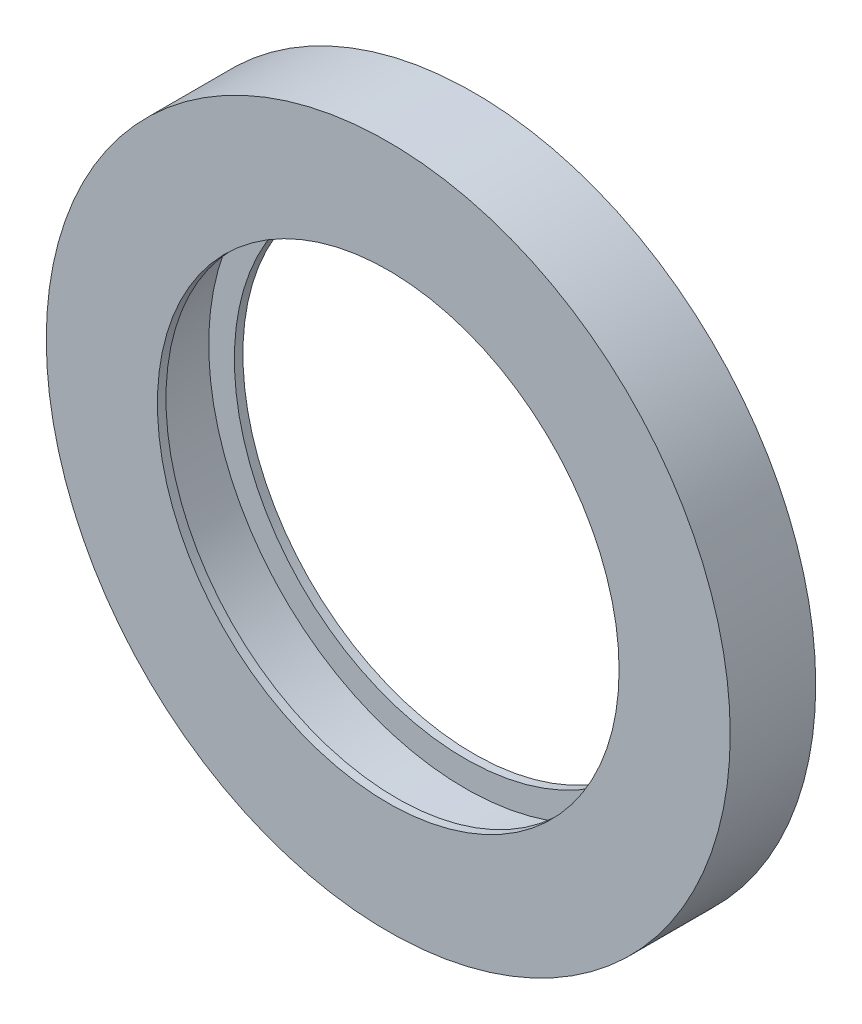
SolidWorks part; units mm, degrees
ref_plane "Front Plane" through (0, 0, 0) normal (0, 0, 1) x (1, 0, 0)
ref_plane "Top Plane" through (0, 0, 0) normal (0, 1, 0) x (1, 0, 0)
ref_plane "Right Plane" through (0, 0, 0) normal (1, 0, 0) x (0, 0, -1)
sketch "Sketch1" plane through (0, 0, 0) normal (0, 0, 1) x (1, 0, 0)
  circle A0 centre (0, 0) radius 40
  circle A1 centre (0, 0) radius 30
  dimension "D1" = 80
  dimension "D2" = 10
extrude "Boss-Extrude1" add sketch "Sketch1" along normal blind 10
sketch "Sketch2" plane through (0, 0, 10) normal (0, 0, 1) x (1, 0, 0)
  circle A0 centre (0, 0) radius 30
  circle A1 centre (0, 0) radius 27
  circle A2 centre (0, 0) radius 30 construction
  dimension "D2" = 0
  dimension "D1" = 3
extrude "Boss-Extrude2" add sketch "Sketch2" against normal blind 1
pattern_linear "LPattern1" count 2 spacing 9 along (0, 0, -1) of "Boss-Extrude2"
